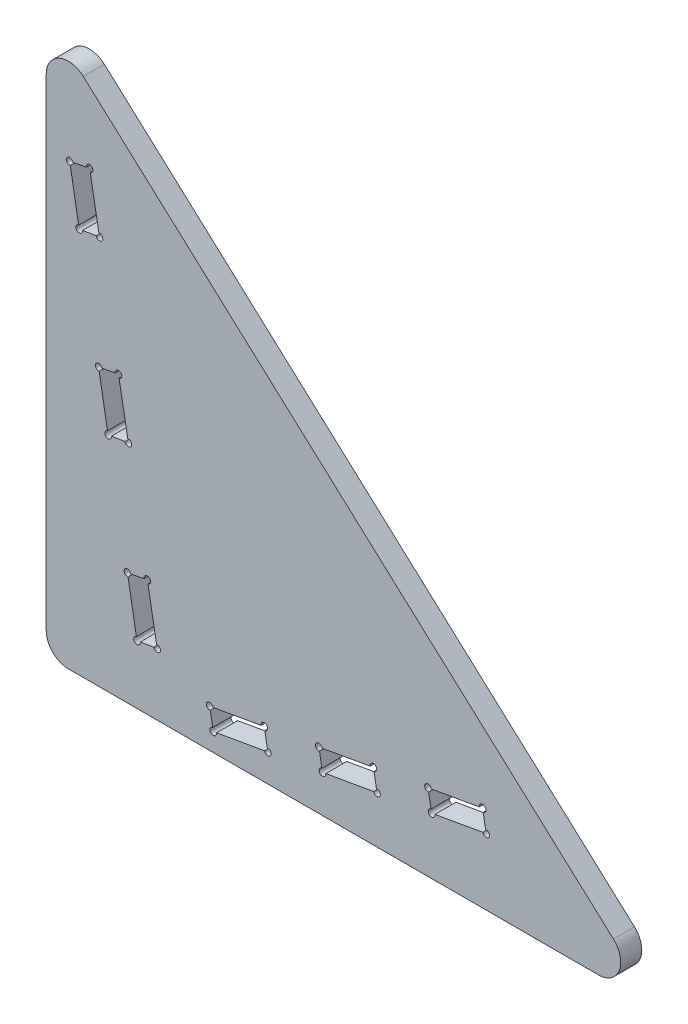
SolidWorks part; units mm, degrees
ref_plane "Front Plane" through (0, 0, 0) normal (0, 0, 1) x (1, 0, 0)
ref_plane "Top Plane" through (0, 0, 0) normal (0, 1, 0) x (1, 0, 0)
ref_plane "Right Plane" through (0, 0, 0) normal (1, 0, 0) x (0, 0, -1)
sketch "Sketch1" plane through (0, 0, 0) normal (0, 0, 1) x (1, 0, 0)
  line L0 (0, 20) -> (0, 454.789)
  line L1 (33.4535, 469.5878) -> (511.7213, 34.7988)
  line L2 (498.2679, 0) -> (20, 0)
  line L3 (34.0962, 390.1571) -> (34.0962, 360.3341) construction
  line L4 (24.1306, 397.736) -> (36.207, 400.0745)
  line L5 (21.7062, 394.2113) -> (29.2556, 351.3967)
  line L6 (32.7369, 348.9283) -> (45.0718, 350.9535)
  line L7 (39.6851, 397.6925) -> (47.4993, 354.3919)
  line L8 (50.1778, 250.0149) -> (62.2542, 252.3533)
  line L9 (47.7535, 246.4901) -> (55.3028, 203.6756)
  line L10 (58.7841, 201.2072) -> (71.119, 203.2324)
  line L11 (65.7323, 249.9713) -> (73.5466, 206.6707)
  line L12 (60.1434, 242.4359) -> (60.1434, 212.6129) construction
  line L13 (76.225, 102.2937) -> (88.3015, 104.6321)
  line L14 (73.8007, 98.769) -> (81.35, 55.9544)
  line L15 (84.8314, 53.486) -> (97.1662, 55.5112)
  line L16 (91.7795, 102.2501) -> (99.5938, 58.9496)
  line L17 (86.1906, 94.7148) -> (86.1906, 64.8917) construction
  line L18 (174.1013, 30.8442) -> (188.3494, 30.8442) construction
  line L21 (0, 0) -> (11.2983, 1.9922) construction
  line L22 (248.9211, 52.4853) -> (292.2526, 60.1258)
  line L23 (150.4403, 35.1205) -> (193.7718, 42.761)
  line L24 (148.0068, 31.6451) -> (150.1774, 19.335)
  line L25 (153.6528, 16.9015) -> (196.9843, 24.5421)
  line L26 (197.2472, 40.3275) -> (199.4178, 28.0174)
  line L27 (370.7907, 65.406) -> (371.4133, 65.5158) construction
  line L29 (246.4876, 49.0099) -> (248.6582, 36.6998)
  line L30 (252.1336, 34.2664) -> (295.4651, 41.9069)
  line L31 (295.728, 57.6923) -> (297.8986, 45.3822)
  line L33 (272.31, 48.0412) -> (272.5821, 48.209) construction
  line L34 (347.4018, 69.8501) -> (390.7334, 77.4906)
  line L35 (344.9684, 66.3748) -> (347.139, 54.0647)
  line L36 (350.6143, 51.6312) -> (393.9459, 59.2717)
  line L37 (394.2087, 75.0572) -> (396.3794, 62.7471)
  line L38 (371.0629, 65.5738) -> (371.4133, 65.5158) construction
  line L39 (370.7907, 65.406) -> (371.0629, 65.5738) construction
  line L40 (65.1995, 252.9236) -> (74.0793, 203.7184) [skipped]
  line L41 (47.2325, 249.4445) -> (65.1995, 252.9236) [skipped]
  line L42 (47.2325, 249.4445) -> (55.8238, 200.7211) [skipped]
  line L43 (55.8238, 200.7211) -> (74.0793, 203.7184) [skipped]
  line L44 (91.2468, 105.2024) -> (100.1266, 55.9973) [skipped]
  line L45 (73.2797, 101.7234) -> (81.871, 53) [skipped]
  line L46 (81.871, 53) -> (100.1266, 55.9973) [skipped]
  line L47 (73.2797, 101.7234) -> (91.2468, 105.2024) [skipped]
  arc A0 (511.7213, 34.7988) -> (498.2679, 0) centre (498.2679, 20) cw
  arc A1 (0, 20) -> (20, 0) centre (20, 20) ccw
  arc A2 (0, 454.789) -> (33.4535, 469.5878) centre (20, 454.789) cw
  arc A3 (24.1306, 397.736) -> (21.7062, 394.2113) centre (21.1853, 397.1657) ccw
  arc A4 (39.6851, 397.6925) -> (36.207, 400.0745) centre (39.1523, 400.6448) ccw
  arc A5 (29.2556, 351.3967) -> (32.7369, 348.9283) centre (29.7765, 348.4423) ccw
  arc A6 (45.0718, 350.9535) -> (47.4993, 354.3919) centre (48.0321, 351.4396) ccw
  arc A7 (50.1778, 250.0149) -> (47.7535, 246.4901) centre (47.2325, 249.4445) ccw
  arc A8 (65.7323, 249.9713) -> (62.2542, 252.3533) centre (65.1995, 252.9236) ccw
  arc A9 (55.3028, 203.6756) -> (58.7841, 201.2072) centre (55.8238, 200.7211) ccw
  arc A10 (71.119, 203.2324) -> (73.5466, 206.6707) centre (74.0793, 203.7184) ccw
  arc A11 (76.225, 102.2937) -> (73.8007, 98.769) centre (73.2797, 101.7234) ccw
  arc A12 (91.7795, 102.2501) -> (88.3015, 104.6321) centre (91.2468, 105.2024) ccw
  arc A13 (97.1662, 55.5112) -> (99.5938, 58.9496) centre (100.1266, 55.9973) ccw
  arc A14 (81.35, 55.9544) -> (84.8314, 53.486) centre (81.871, 53) ccw
  arc A15 (150.4403, 35.1205) -> (148.0068, 31.6451) centre (147.4859, 34.5995) ccw
  arc A16 (150.1774, 19.335) -> (153.6528, 16.9015) centre (150.6984, 16.3806) ccw
  arc A17 (197.2472, 40.3275) -> (193.7718, 42.761) centre (196.7263, 43.2819) ccw
  arc A18 (196.9843, 24.5421) -> (199.4178, 28.0174) centre (199.9387, 25.063) ccw
  arc A19 (295.4651, 41.9069) -> (297.8986, 45.3822) centre (298.4195, 42.4278) ccw
  arc A20 (295.728, 57.6923) -> (292.2526, 60.1258) centre (295.207, 60.6468) ccw
  arc A21 (248.6582, 36.6998) -> (252.1336, 34.2664) centre (249.1791, 33.7454) ccw
  arc A22 (248.9211, 52.4853) -> (246.4876, 49.0099) centre (245.9666, 51.9644) ccw
  arc A23 (393.9459, 59.2717) -> (396.3794, 62.7471) centre (396.9003, 59.7926) ccw
  arc A24 (394.2087, 75.0572) -> (390.7334, 77.4906) centre (393.6878, 78.0116) ccw
  arc A25 (347.139, 54.0647) -> (350.6143, 51.6312) centre (347.6599, 51.1102) ccw
  arc A26 (347.4018, 69.8501) -> (344.9684, 66.3748) centre (344.4474, 69.3292) ccw
  point P6 (550, 0)
  point P9 (0, 0)
  point P12 (0, 500)
  point P13 (34.0962, 374.5878)
  point P19 (60.1434, 226.8666)
  point P24 (86.1906, 79.1454)
  point P25 (60.1434, 226.8666)
  point P29 (174.1013, 30.8442)
  point P30 (174.1013, 30.8442)
  point P37 (272.5821, 48.209)
  point P38 (272.5821, 48.209)
  point P43 (371.0629, 65.5738)
  point P44 (371.0629, 65.5738)
  point P53 (86.1906, 79.1454)
  dimension "D3" = 20
  dimension "D1" = 500
  dimension "D2" = 550
  dimension "D4" = 3
  dimension "D5" = 50
  dimension "D6" = 18.5
  dimension "D7" = 50
  dimension "D9" = 18.5
  dimension "D11" = 10
  dimension "D12" = 3
  dimension "D13" = 10
  dimension "D10" = 3
extrude "Boss-Extrude1" add sketch "Sketch1" along normal blind 19
